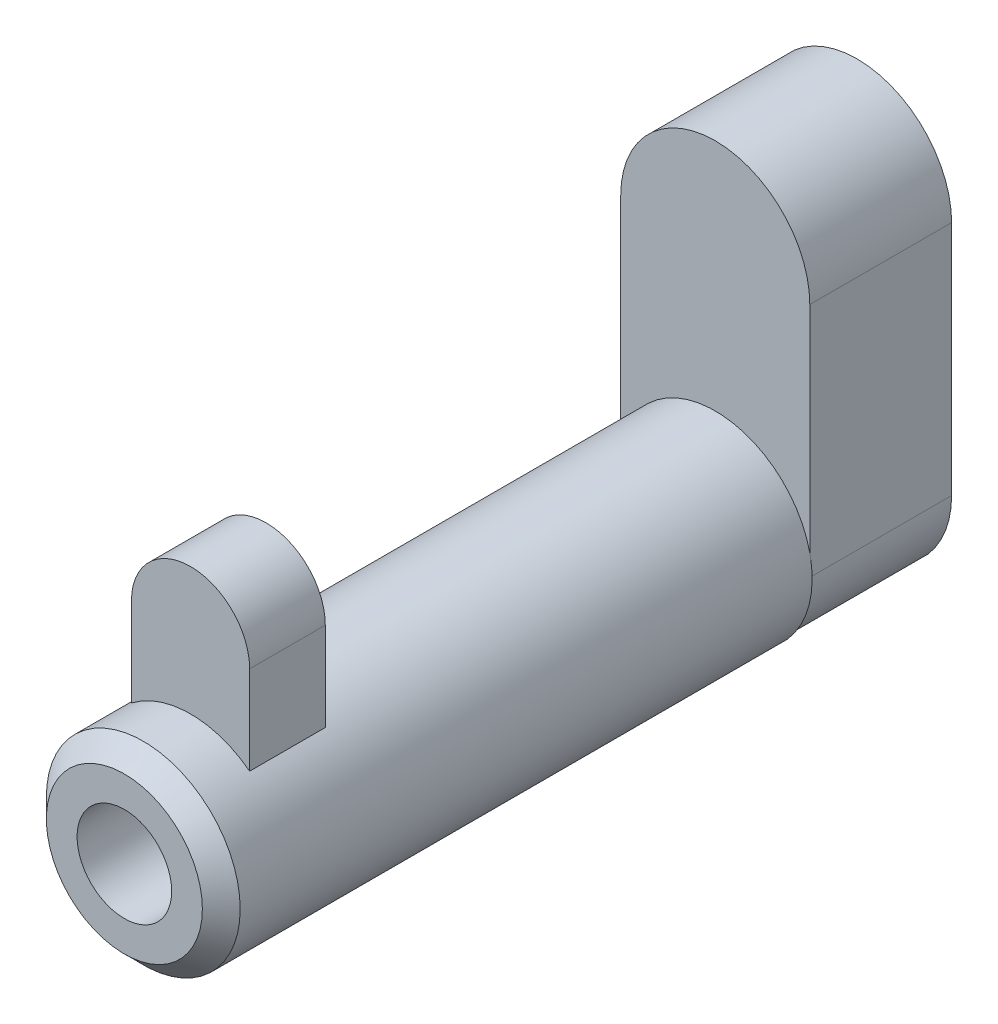
SolidWorks part; units mm, degrees
ref_plane "Ebene vorne" through (0, 0, 0) normal (0, 0, 1) x (1, 0, 0)
ref_plane "Ebene oben" through (0, 0, 0) normal (0, 1, 0) x (1, 0, 0)
ref_plane "Ebene rechts" through (0, 0, 0) normal (1, 0, 0) x (0, 0, -1)
sketch "Skizze1" plane through (0, 0, 0) normal (0, 0, 1) x (1, 0, 0)
  line L0 (2, 0) -> (2, 5)
  line L1 (-2, 5) -> (-2, 0)
  arc A1 (2, 0) -> (-2, 0) centre (0, 0) cw
  arc A2 (2, 5) -> (-2, 5) centre (0, 5) ccw
  point P7 (14.3687, 0.6876)
  point P8 (0, 0)
  point P10 (3.3461, 3.6241)
  dimension "D1" = 4
  dimension "D2" = 5
extrude "Aufsatz-Linear austragen1" add sketch "Skizze1" along normal blind 3
sketch "Skizze2" plane through (0, 0, 3) normal (0, 0, 1) x (1, 0, 0)
  circle A0 centre (0, 0) radius 2.05
  arc A1 (-2, 0) -> (2, 0) centre (0, 0) ccw construction
  point P3 (17.4741, 0)
  dimension "D1" = 4.1
extrude "Aufsatz-Linear austragen2" add sketch "Skizze2" along normal blind 12.5
sketch "Skizze3" plane through (0, 0, 3) normal (0, 0, 1) x (1, 0, 0)
  line L0 (0, 0) -> (0, 3.5) construction
  line L1 (-1.25, 1.6248) -> (-1.25, 3.5)
  line L2 (1.25, 1.6248) -> (1.25, 3.5)
  arc A0 (-1.25, 3.5) -> (1.25, 3.5) centre (0, 3.5) cw
  circle A1 centre (0, 0) radius 2.05
  circle A2 centre (0, 0) radius 2.05
  dimension "D2" = 3.5
  dimension "D3" = 2.5
  dimension "D1" = 0
extrude "Aufsatz-Linear austragen3" add sketch "Skizze3" along normal blind 1.6 from offset 9.5
sketch "Skizze4" plane through (0, 0, 15.5) normal (0, 0, 1) x (1, 0, 0)
  circle A1 centre (0, 0) radius 1
  dimension "D1" = 2
extrude "Schnitt-Linear austragen1" cut sketch "Skizze4" against normal up to next
chamfer "Fase1" distance 0.4 angle 45 1 edges at (2.05, 0, 15.5)
